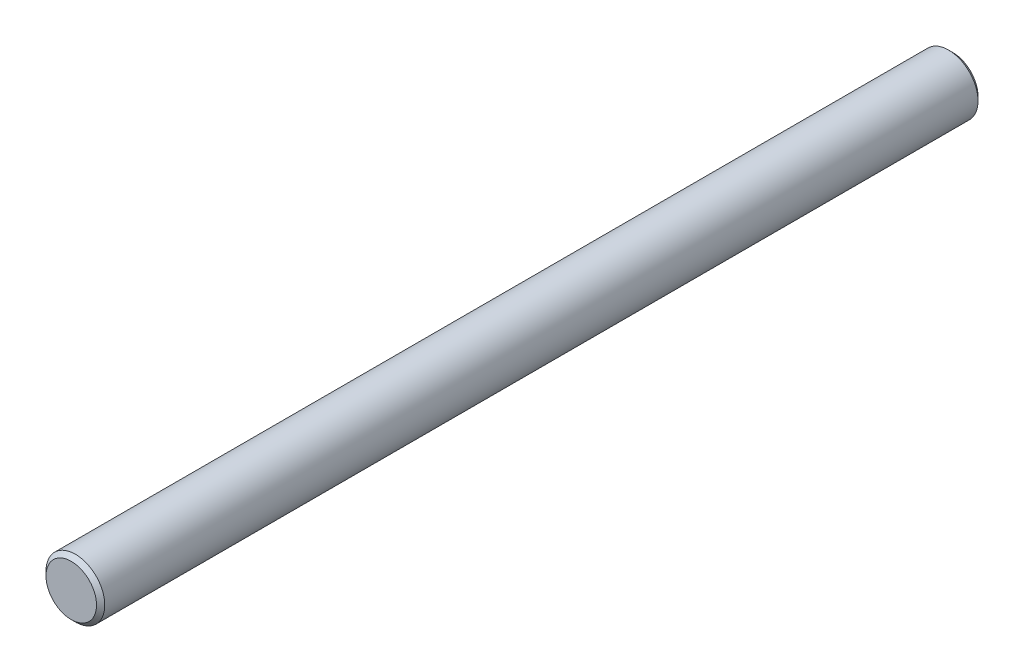
SolidWorks part; units mm, degrees
ref_plane "Front Plane" through (0, 0, 0) normal (0, 0, 1) x (1, 0, 0)
ref_plane "Top Plane" through (0, 0, 0) normal (0, 1, 0) x (1, 0, 0)
ref_plane "Right Plane" through (0, 0, 0) normal (1, 0, 0) x (0, 0, -1)
sketch "Sketch1" plane through (0, 0, 0) normal (0, 0, 1) x (1, 0, 0)
  line L0 (-4, 0) -> (4, 0) construction
  line L5 (0, 4) -> (0, -4) construction
  circle A1 centre (0, 0) radius 4
  point P7 (-4, 0)
  point P8 (4, 0)
  point P12 (0, -4)
  point P13 (0, 4)
  dimension "Diameter" = 8
sketch "Sketch2" plane through (0, 0, 0) normal (1, 0, 0) x (0, 0, -1)
  line L0 (-52, -4) -> (-52, 4) construction
  line L1 (60, -4) -> (-60, -4)
  line L2 (60, -4) -> (60, 4)
  line L3 (60, 4) -> (-60, 4)
  line L4 (-60, -4) -> (-60, 4)
  line L5 (60, -4) -> (-60, 4) construction
  line L6 (60, 4) -> (-60, -4) construction
  line L7 (52, -4) -> (52, 4) construction
  line L8 (-60, 3.44) -> (-59.44, 4) construction
  point P0 (0, 0)
  point P8 (-60, 4)
  point P9 (60, 4)
  point P14 (-52, 4)
  point P15 (-52, -4)
  point P16 (52, 4)
  point P17 (52, -4)
  point P25 (0, -4)
  dimension "Length" = 120
  dimension "D1" = 8
  dimension "D2" = 8
  dimension "Chamfer Typ," = 45
  dimension "D4" = 0.56
sketch "Sketch3" plane through (0, 0, 0) normal (0, 0, 1) x (1, 0, 0)
  circle A0 centre (0, 0) radius 4 construction
  circle A1 centre (0, 0) radius 4
extrude "Boss-Extrude1" add sketch "Sketch3" along normal up to vertex (60 mm away) and the other way up to vertex (60 mm away) up to point (0, 4, 60) other way up to point (0, 4, -60)
chamfer "Chamfer1" distance 0.56 angle 45 2 edges at (4, 0, -60) (4, 0, 60)
equation "\"D1@Sketch2\"=\"Diameter@Sketch1\""
equation "\"D2@Sketch2\"=\"Diameter@Sketch1\""
equation "\"D1@Chamfer1\"=\"Diameter@Sketch1\"*.07"
equation "\"D4@Sketch2\"=\"Diameter@Sketch1\"*.07"
equation "\"D2@Chamfer1\"=\"Chamfer Typ,@Sketch2\""
